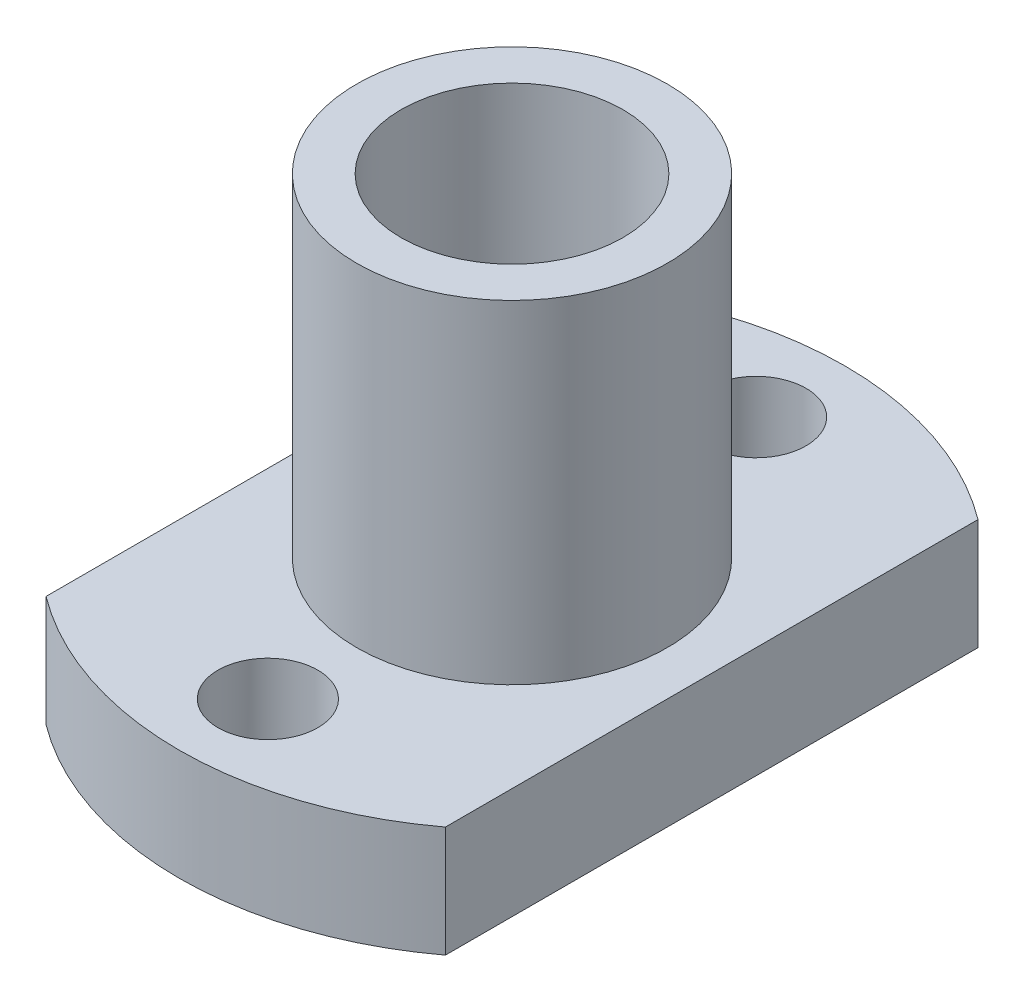
SolidWorks part; units mm, degrees
material "3.0205 (EN-AW 1200)"
ref_plane "Plan de face" through (0, 0, 0) normal (0, 0, 1) x (1, 0, 0)
ref_plane "Plan de dessus" through (0, 0, 0) normal (0, 1, 0) x (1, 0, 0)
ref_plane "Plan de droite" through (0, 0, 0) normal (1, 0, 0) x (0, 0, -1)
sketch "Esquisse1" plane through (0, 0, 0) normal (0, 1, 0) x (1, 0, 0)
  line L0 (-9, 12) -> (-9, -12)
  line L1 (9, 12) -> (9, -12)
  arc A0 (-9, 12) -> (9, 12) centre (0, 0) cw
  arc A1 (-9, -12) -> (9, -12) centre (0, 0) ccw
  point P2 (0, 0)
  point P10 (0, 15)
  point P11 (0, -15)
  point P12 (-9, 0)
  dimension "D1" = 18
  dimension "D2" = 30
extrude "Boss.-Extru.1" add sketch "Esquisse1" along normal blind 5
sketch "Esquisse2" plane through (0, 5, 0) normal (0, 1, 0) x (1, 0, 0)
  circle A0 centre (0, 0) radius 7
  dimension "D1" = 14
extrude "Boss.-Extru.2" add sketch "Esquisse2" along normal blind 15
sketch "Esquisse3" plane through (0, 20, 0) normal (0, 1, 0) x (1, 0, 0)
  circle A0 centre (0, 0) radius 5
  dimension "D1" = 10
extrude "Enlèv. mat.-Extru.1" cut sketch "Esquisse3" against normal blind 30
sketch "Esquisse4" plane through (0, 5, 0) normal (0, 1, 0) x (1, 0, 0)
  circle A0 centre (0, 0) radius 11 construction
  circle A1 centre (0, 11) radius 2.25
  circle A2 centre (0, -11) radius 2.25
  point P7 (0, 11)
  point P8 (0, -11)
  point P9 (0, 0)
  dimension "D1" = 22
  dimension "D2" = 4.5
  dimension "D3" = 4.5
extrude "Enlèv. mat.-Extru.2" cut sketch "Esquisse4" against normal blind 30
